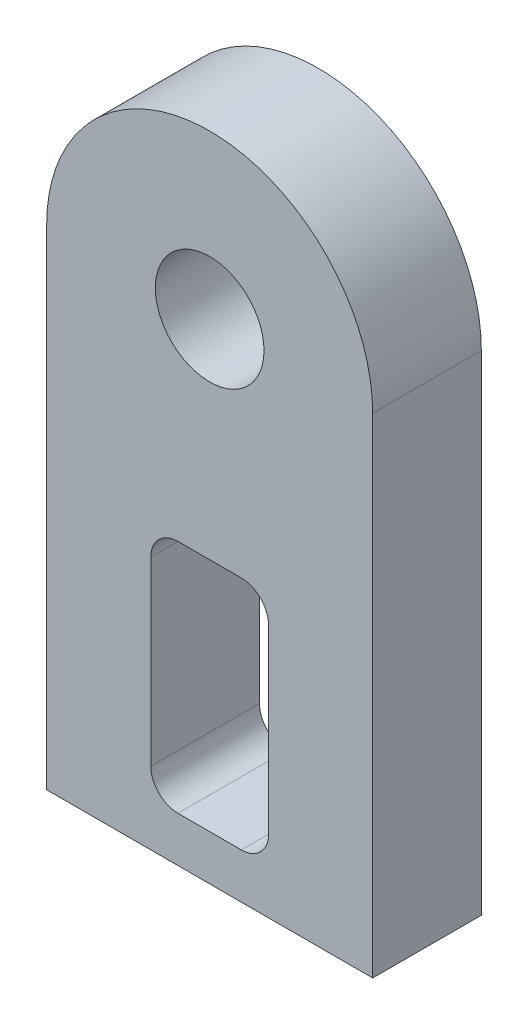
SolidWorks part; units mm, degrees
ref_plane "Alzado" through (0, 0, 0) normal (0, 0, 1) x (1, 0, 0)
ref_plane "Planta" through (0, 0, 0) normal (0, 1, 0) x (1, 0, 0)
ref_plane "Vista lateral" through (0, 0, 0) normal (1, 0, 0) x (0, 0, -1)
sketch "Model" plane through (0, 0, 0) normal (0, 0, 1) x (1, 0, 0)
  line L0 (159.5914, 212.494) -> (159.5914, 198.994)
  line L1 (159.5914, 198.994) -> (150.5914, 198.994)
  line L2 (150.5914, 198.994) -> (150.5914, 212.494)
  line L3 (153.4664, 200.994) -> (153.4664, 205.994)
  line L4 (154.2164, 206.744) -> (155.9664, 206.744)
  line L5 (156.7164, 205.994) -> (156.7164, 200.994)
  line L6 (155.9664, 200.244) -> (154.2164, 200.244)
  circle A0 centre (155.0914, 212.494) radius 1.5
  arc A1 (159.5914, 212.494) -> (150.5914, 212.494) centre (155.0914, 212.494) ccw
  arc A2 (154.2164, 206.744) -> (153.4664, 205.994) centre (154.2164, 205.994) ccw
  arc A3 (156.7164, 205.994) -> (155.9664, 206.744) centre (155.9664, 205.994) ccw
  arc A4 (155.9664, 200.244) -> (156.7164, 200.994) centre (155.9664, 200.994) ccw
  arc A5 (153.4664, 200.994) -> (154.2164, 200.244) centre (154.2164, 200.994) ccw
extrude "Saliente-Extruir1" add sketch "Model" along normal blind 3
